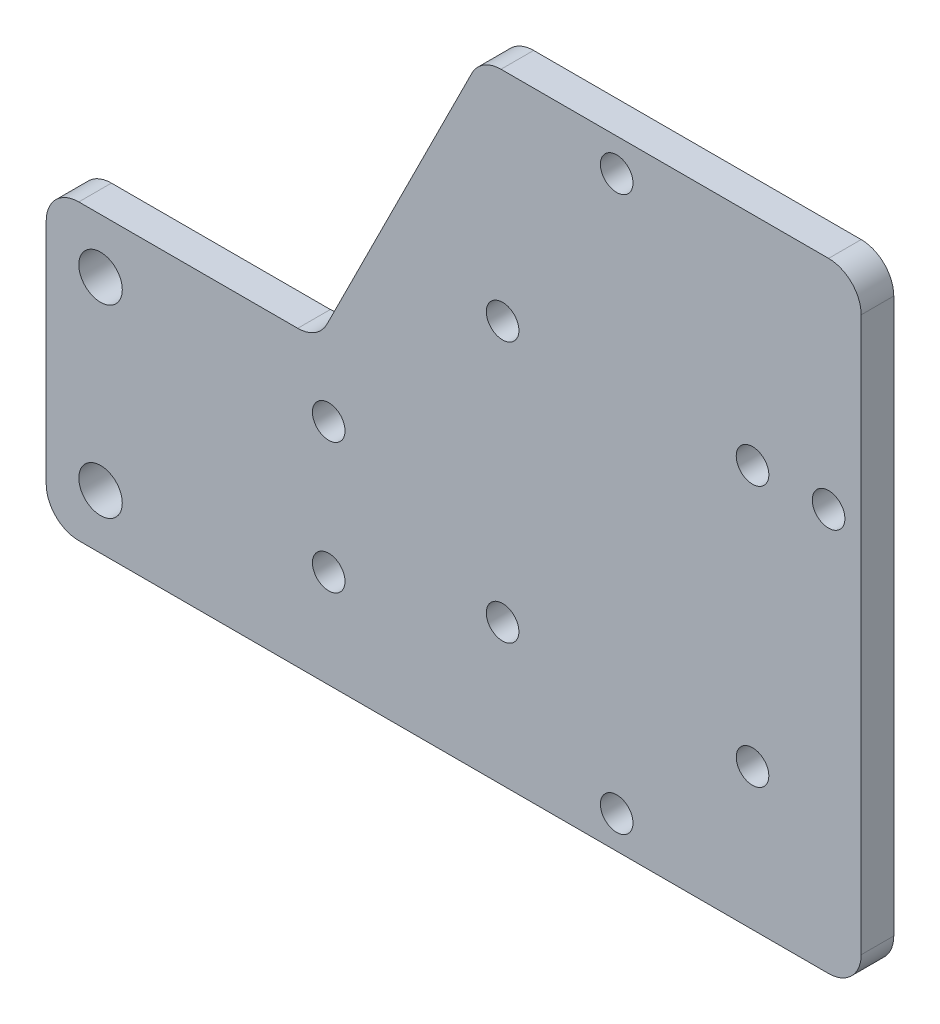
SolidWorks part; units mm, degrees
ref_plane "Plan de face" through (0, 0, 0) normal (0, 0, 1) x (1, 0, 0)
ref_plane "Plan de dessus" through (0, 0, 0) normal (0, 1, 0) x (1, 0, 0)
ref_plane "Plan de droite" through (0, 0, 0) normal (1, 0, 0) x (0, 0, -1)
sketch "Esquisse1" plane through (0, 0, 0) normal (0, 0, 1) x (1, 0, 0)
  line L1 (0, 0) -> (75, 0)
  line L2 (0, 0) -> (0, 27)
  line L3 (40, 57) -> (75, 57)
  line L4 (75, 0) -> (75, 57)
  line L7 (0, 27) -> (25, 27)
  line L8 (40, 57) -> (25, 27)
  dimension "D1" = 75
  dimension "D2" = 27
  dimension "D3" = 57
  dimension "D4" = 25
  dimension "D5" = 40
extrude "Boss.-Extru.1" add sketch "Esquisse1" along normal blind 3
sketch "Esquisse2" plane through (0, 0, 3) normal (0, 0, 1) x (1, 0, 0)
  line L0 (75, 25) -> (53.5, 25) construction
  line L1 (75, 0) -> (75, 57) construction
  line L2 (53.5, 25) -> (53.5, 0) construction
  line L3 (0, 0) -> (75, 0) construction
  line L4 (0, 27) -> (0, 0) construction
  circle A0 centre (42, 37) radius 1.5
  circle A1 centre (42, 13) radius 1.5
  circle A2 centre (65, 13) radius 1.5
  circle A3 centre (65, 37) radius 1.5
  dimension "D1" = 3
  dimension "D2" = 23
  dimension "D3" = 24
  dimension "D4" = 25
  dimension "D5" = 53.5
extrude "Enlèv. mat.-Extru.1" cut sketch "Esquisse2" against normal through all
sketch "Esquisse3" plane through (0, 0, 3) normal (0, 0, 1) x (1, 0, 0)
  line L0 (75, 0) -> (75, 57) construction
  line L1 (75, 57) -> (40, 57) construction
  line L2 (0, 0) -> (75, 0) construction
  line L3 (0, 27) -> (0, 0) construction
  line L4 (5, 22) -> (5, 5) construction
  line L5 (5, 13.5) -> (0, 13.5) construction
  circle A0 centre (5, 22) radius 2
  circle A1 centre (5, 5) radius 2
  circle A2 centre (52.5, 3) radius 1.5
  circle A3 centre (52.5, 54) radius 1.5
  circle A4 centre (72, 37) radius 1.5
  dimension "D1" = 22.5
  dimension "D2" = 3
  dimension "D3" = 3
  dimension "D4" = 3
  dimension "D5" = 20
  dimension "D6" = 3
  dimension "D7" = 5
  dimension "D8" = 17
  dimension "D9" = 5
  dimension "D10" = 4
extrude "Enlèv. mat.-Extru.2" cut sketch "Esquisse3" against normal through all contours A3
fillet "Congé1" radius 3 6 edges at (0, 27, 1.5) (25, 27, 1.5) (40, 57, 1.5) (75, 0, 1.5) (0, 0, 1.5) (75, 57, 1.5)
sketch "Esquisse4" plane through (0, 0, 3) normal (0, 0, 1) x (1, 0, 0)
  line L0 (23.1459, 27) -> (3, 27) construction
  line L1 (0, 24) -> (0, 3) construction
  circle A0 centre (26, 21) radius 1.5
  circle A1 centre (26, 9) radius 1.5
  dimension "D1" = 6
  dimension "D2" = 12
  dimension "D3" = 3
  dimension "D4" = 26
extrude "Enlèv. mat.-Extru.3" cut sketch "Esquisse4" against normal through all
